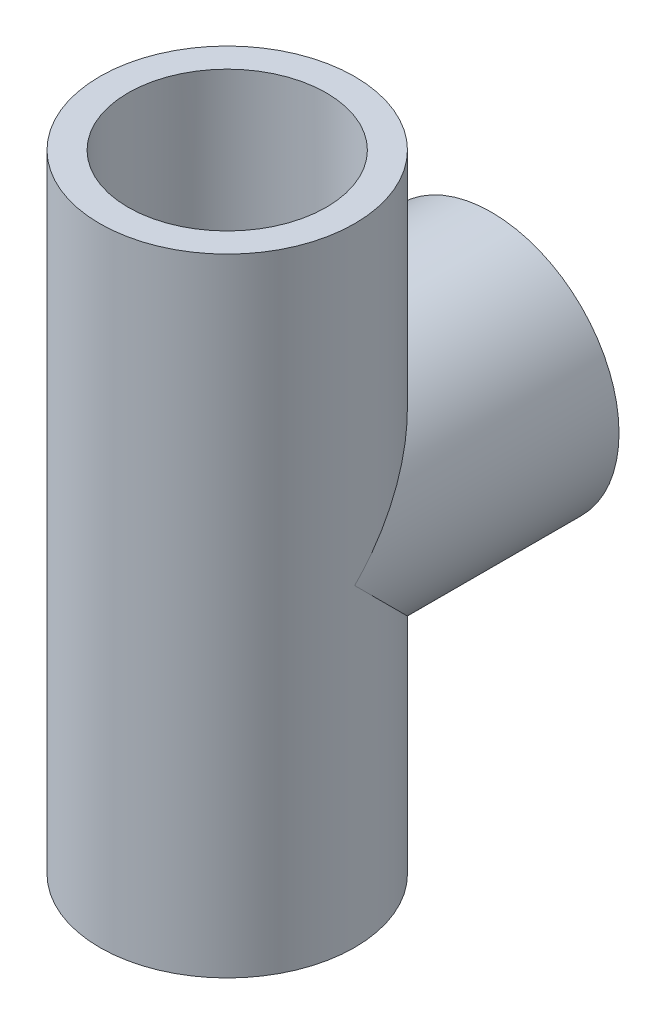
SolidWorks part; units mm, degrees
ref_plane "Front Plane" through (0, 0, 0) normal (0, 0, 1) x (1, 0, 0)
ref_plane "Top Plane" through (0, 0, 0) normal (0, 1, 0) x (1, 0, 0)
ref_plane "Right Plane" through (0, 0, 0) normal (1, 0, 0) x (0, 0, -1)
sketch "Sketch1" plane through (0, 0, 0) normal (0, 1, 0) x (1, 0, 0)
  circle A0 centre (0, 0) radius 13.335
  circle A1 centre (0, 0) radius 17.145
  dimension "D1" = 34.29
  dimension "D2" = 3.81
extrude "Boss-Extrude1" add sketch "Sketch1" along normal blind 84.328
sketch "Sketch2" plane through (0, 0, 0) normal (0, 0, 1) x (1, 0, 0)
  line L0 (-17.145, 0) -> (17.145, 84.328) construction
  circle A0 centre (0, 42.164) radius 17.145
  circle A1 centre (0, 42.164) radius 13.335
  dimension "D1" = 3.81
  dimension "D2" = 34.29
extrude "Boss-Extrude2" add sketch "Sketch2" against normal blind 35.56
sketch "Sketch3" plane through (0, 84.328, 0) normal (0, 1, 0) x (1, 0, 0)
  circle A0 centre (0, 0) radius 13.335
extrude "Cut-Extrude1" cut sketch "Sketch3" against normal through all
sketch "Sketch4" plane through (0, 0, -35.56) normal (0, 0, -1) x (-1, 0, 0)
  circle A0 centre (0, 42.164) radius 13.335 construction
  circle A1 centre (0, 42.164) radius 13.335
extrude "Cut-Extrude2" cut sketch "Sketch4" against normal blind 35.56
